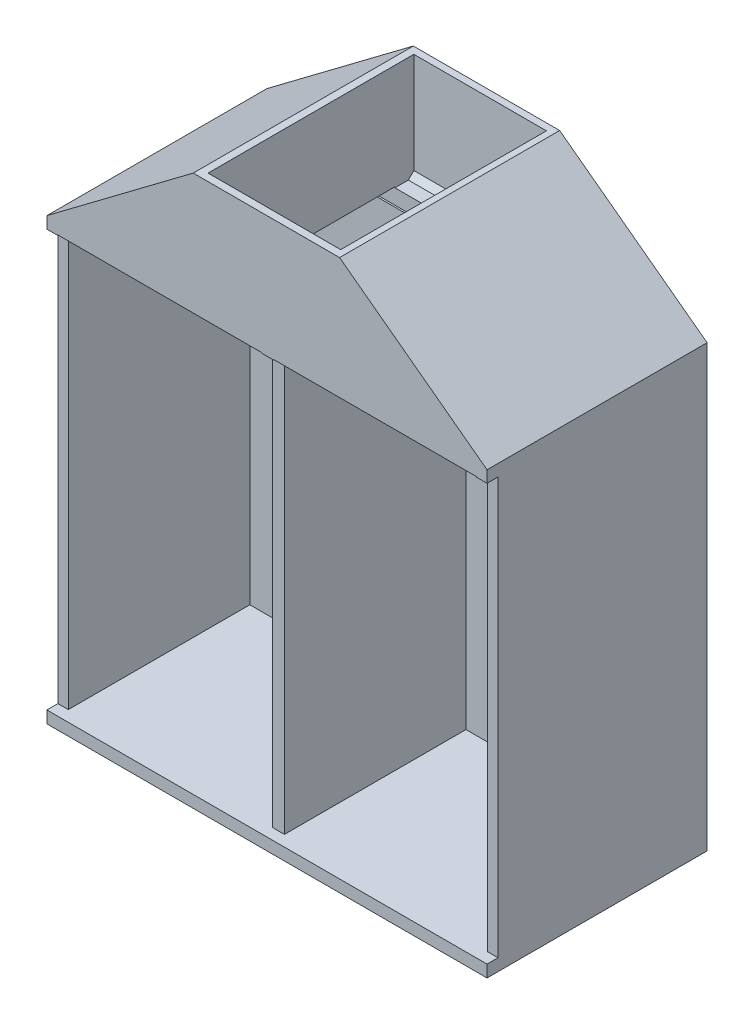
SolidWorks part; units mm, degrees
ref_plane "Front Plane" through (0, 0, 0) normal (0, 0, 1) x (1, 0, 0)
ref_plane "Top Plane" through (0, 0, 0) normal (0, 1, 0) x (1, 0, 0)
ref_plane "Right Plane" through (0, 0, 0) normal (1, 0, 0) x (0, 0, -1)
sketch "Sketch1" plane through (0, 0, 0) normal (0, 0, 1) x (1, 0, 0)
  line L0 (-56.7571, -21.9029) -> (743.2429, -21.9029)
  line L1 (-56.7571, -21.9029) -> (-56.7571, 778.0971)
  line L3 (743.2429, 778.0971) -> (743.2429, -21.9029)
  line L6 (209.2429, 978.0971) -> (475.2429, 978.0971)
  line L9 (743.2429, 778.0971) -> (475.2429, 978.0971)
  line L10 (209.2429, 978.0971) -> (-56.7571, 778.0971)
  line L11 (333.4629, -21.9029) -> (355.0002, -21.9029)
  line L13 (355.0002, 978.0971) -> (333.4629, 978.0971)
  line L15 (-37.8859, 757.753) -> (333.4629, 757.753)
  line L16 (209.2429, 958.0971) -> (333.4629, 958.0971)
  line L17 (333.4629, 778.0971) -> (-23.4771, 778.0971)
  line L18 (333.4629, 958.0971) -> (333.4629, 778.0971)
  line L19 (475.2429, 958.0971) -> (355.0002, 958.0971)
  line L20 (707.6033, 778.0971) -> (475.2429, 958.0971)
  line L21 (-23.4771, 778.0971) -> (209.2429, 958.0971)
  line L22 (355.0002, 958.0971) -> (355.0002, 778.0971)
  line L23 (355.0002, 0) -> (355.0002, 757.753)
  line L24 (-37.8859, 757.753) -> (-37.8859, 540.9208)
  line L25 (-37.8859, 0) -> (333.4629, 0)
  line L26 (-37.8859, 0) -> (-37.8859, 540.9208)
  line L27 (333.4629, 0) -> (333.4629, 757.753)
  line L28 (724.1773, 757.753) -> (724.1773, 462.33)
  line L29 (724.1773, 0) -> (724.1773, 462.33)
  line L30 (724.1773, 0) -> (355.0002, 0)
  line L31 (355.0002, 778.0971) -> (707.6033, 778.0971)
  line L32 (355.0002, 757.753) -> (724.1773, 757.753)
extrude "Boss-Extrude2" add sketch "Sketch1" along normal blind 400 contours L32 L23 L30 L29 L28 | L25 L27 L15 L24 L26 | L6 L9 L3 L0 L1 L10
sketch "Sketch2" plane through (0, 0, 0) normal (0, 1, 0) x (1, 0, 0)
  line L0 (-37.8859, 0) -> (724.1773, 0)
  line L1 (724.1773, 0) -> (724.1773, -50)
  line L2 (724.1773, -400) -> (724.1773, 0) construction
  line L3 (724.1773, -50) -> (-37.8859, -50)
  line L4 (-37.8859, -400) -> (-37.8859, 0) construction
  line L5 (-37.8859, -50) -> (-37.8859, 0)
extrude "Boss-Extrude3" add sketch "Sketch2" along normal blind 761
sketch "Sketch3" plane through (0, 0, 400) normal (0, 0, 1) x (1, 0, 0)
  line L0 (-56.7571, 756.7692) -> (743.2429, 756.7692)
  line L1 (-56.7571, -21.9029) -> (-56.7571, 778.0971) construction
  line L2 (743.2429, 778.0971) -> (743.2429, -21.9029) construction
  line L3 (743.2429, 756.7692) -> (743.2429, 0)
  line L4 (743.2429, 0) -> (-56.7571, 0)
  line L5 (-56.7571, 0) -> (-56.7571, 756.7692)
extrude "Cut-Extrude1" cut sketch "Sketch3" against normal blind 20
sketch "Sketch4" plane through (0, 978.0971, 0) normal (0, 1, 0) x (1, 0, 0)
  line L1 (222.7431, -12.5559) -> (463.7426, -12.5559)
  line L2 (222.7431, -12.5559) -> (222.7431, -386.5515)
  line L3 (222.7431, -386.5515) -> (463.7426, -386.5515)
  line L4 (463.7426, -12.5559) -> (463.7426, -386.5515)
extrude "Cut-Extrude2" cut sketch "Sketch4" against normal blind 164
sketch "Sketch5" plane through (0, 757.753, 0) normal (0, -1, 0) x (1, 0, 0)
  line L3 (331.6917, 46.9469) -> (-35.0581, 46.9469)
  line L4 (-35.0581, 379.0432) -> (-35.0581, 46.9469)
  line L5 (-35.0581, 379.0432) -> (331.6917, 379.0432)
  line L6 (331.6917, 379.0432) -> (331.6917, 46.9469)
extrude "Cut-Extrude4" cut sketch "Sketch5" against normal blind 29
sketch "Sketch6" plane through (0, 814.0971, 0) normal (0, 1, 0) x (1, 0, 0)
  line L0 (222.7431, -386.5515) -> (463.7426, -386.5515) construction
  line L1 (222.7431, -12.5559) -> (463.7426, -12.5559)
  line L2 (222.7431, -12.5559) -> (222.7431, -386.5515)
  line L3 (222.7431, -386.5515) -> (463.7426, -386.5515)
  line L4 (463.7426, -12.5559) -> (463.7426, -386.5515)
  line L5 (463.7426, -386.5515) -> (463.7426, -12.5559) construction
extrude "Cut-Extrude5" cut sketch "Sketch6" against normal blind 29
sketch "Sketch7" plane through (0, 757.753, 0) normal (0, -1, 0) x (1, 0, 0)
  line L1 (726.1643, 50.2161) -> (353.954, 50.2161)
  line L2 (726.1643, 50.2161) -> (726.1643, 378.2638)
  line L3 (726.1643, 378.2638) -> (353.954, 378.2638)
  line L4 (353.954, 50.2161) -> (353.954, 378.2638)
extrude "Cut-Extrude7" cut sketch "Sketch7" against normal blind 29
chamfer "Chamfer2" distance 10 angle 45 3 edges at (343.2429, 785.0971, 12.5559) (331.6917, 785.0971, 212.9951) (353.954, 785.0971, 214.2399)
